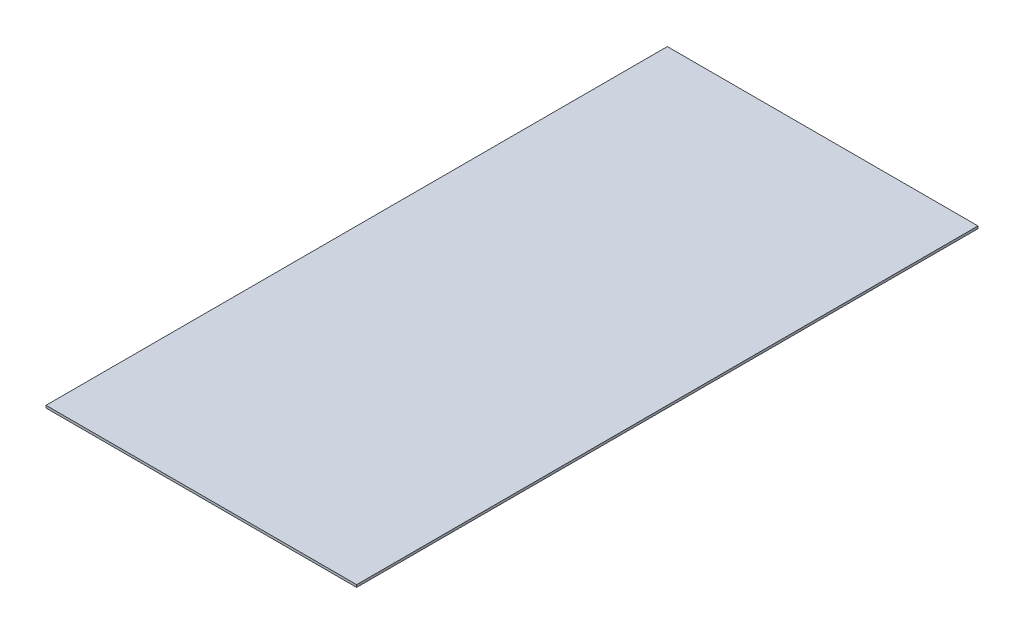
SolidWorks part; units mm, degrees
material "ASTM A36 Acero"
ref_plane "Alzado" through (0, 0, 0) normal (0, 0, 1) x (1, 0, 0)
ref_plane "Planta" through (0, 0, 0) normal (0, 1, 0) x (1, 0, 0)
ref_plane "Vista lateral" through (0, 0, 0) normal (1, 0, 0) x (0, 0, -1)
sketch "Croquis1" plane through (0, 0, 0) normal (0, 1, 0) x (1, 0, 0)
  line L1 (-609.6, -1219.2) -> (609.6, -1219.2)
  line L2 (-609.6, -1219.2) -> (-609.6, 1219.2)
  line L3 (-609.6, 1219.2) -> (609.6, 1219.2)
  line L4 (609.6, -1219.2) -> (609.6, 1219.2)
  line L5 (-609.6, -1219.2) -> (609.6, 1219.2) construction
  line L6 (-609.6, 1219.2) -> (609.6, -1219.2) construction
  point P0 (0, 0)
  dimension "D1" = 2438.4
  dimension "D2" = 1219.2
extrude "Saliente-Extruir1" add sketch "Croquis1" along normal blind 9.5
